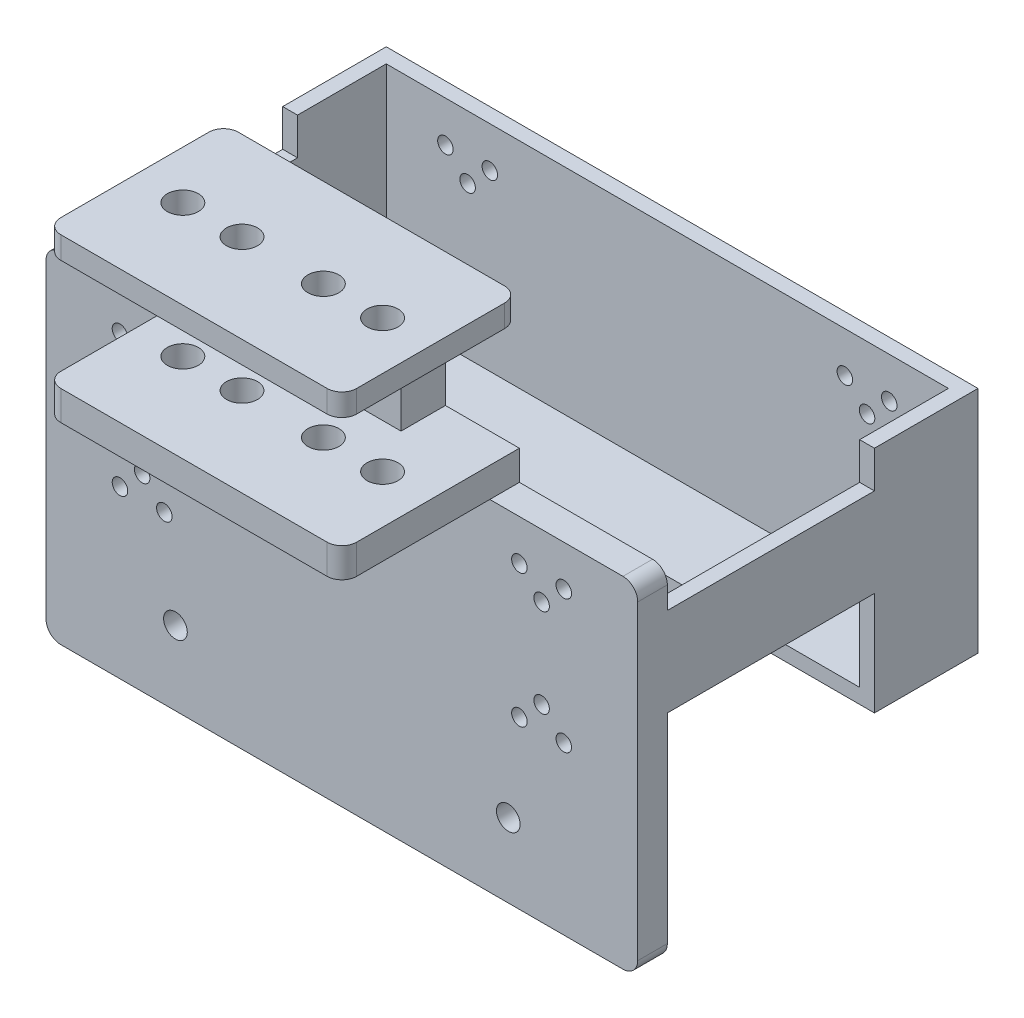
SolidWorks part; units mm, degrees
ref_plane "前视基准面" through (0, 0, 0) normal (0, 0, 1) x (1, 0, 0)
ref_plane "上视基准面" through (0, 0, 0) normal (0, 1, 0) x (1, 0, 0)
ref_plane "右视基准面" through (0, 0, 0) normal (1, 0, 0) x (0, 0, -1)
other "Configuration Table"
sketch "草图1" plane through (0, 0, 0) normal (0, 0, 1) x (1, 0, 0)
  line L1 (-40, 14.5) -> (40, 14.5)
  line L2 (-40, 14.5) -> (-40, -14.5)
  line L3 (-40, -14.5) -> (40, -14.5)
  line L4 (40, 14.5) -> (40, -14.5)
  line L5 (-40, 14.5) -> (40, -14.5) construction
  line L6 (-40, -14.5) -> (40, 14.5) construction
  point P0 (0, 0)
extrude "凸台-拉伸1" add sketch "草图1" along normal blind 2
sketch "草图4" plane through (0, 0, 2) normal (0, 0, 1) x (1, 0, 0)
  line L0 (40, -14.5) -> (40, 14.5) construction
  line L1 (40, 14.5) -> (38, 14.5)
  line L2 (40, 14.5) -> (40, -14.5)
  line L3 (40, -14.5) -> (38, -14.5)
  line L4 (38, 14.5) -> (38, -14.5)
  line L5 (40, 14.5) -> (-40, 14.5) construction
  line L6 (-40, -14.5) -> (40, -14.5) construction
  line L8 (-40, 14.5) -> (-38, 14.5)
  line L9 (-40, 14.5) -> (-40, -14.5)
  line L10 (-40, -14.5) -> (-38, -14.5)
  line L11 (-38, 14.5) -> (-38, -14.5)
  dimension "D1" = 2
  dimension "D2" = 2
extrude "凸台-拉伸2" add sketch "草图4" along normal blind 12
sketch "草图6" plane through (0, -14.5, 0) normal (0, -1, 0) x (1, 0, 0)
  line L1 (-40, 0) -> (40, 0)
  line L2 (-40, 0) -> (-40, 14)
  line L3 (-40, 14) -> (40, 14)
  line L4 (40, 0) -> (40, 14)
extrude "凸台-拉伸4" add sketch "草图6" along normal blind 2
sketch "草图7" plane through (0, 0, 14) normal (0, 0, 1) x (1, 0, 0)
  line L0 (-40, 14.5) -> (-40, -16.5) construction
  line L1 (-40, 9.5) -> (-38, 9.5)
  line L2 (-40, 9.5) -> (-40, -2.5)
  line L3 (-40, -2.5) -> (-38, -2.5)
  line L4 (-38, 9.5) -> (-38, -2.5)
  line L5 (-38, -14.5) -> (-38, 14.5) construction
  line L6 (-38, 14.5) -> (-40, 14.5) construction
  line L7 (38, 14.5) -> (38, -14.5) construction
  line L8 (38, 9.5) -> (40, 9.5)
  line L9 (38, 9.5) -> (38, -2.5)
  line L10 (38, -2.5) -> (40, -2.5)
  line L11 (40, 9.5) -> (40, -2.5)
  line L12 (40, -16.5) -> (40, 14.5) construction
  dimension "D1" = 5
  dimension "D2" = 12
extrude "凸台-拉伸5" add sketch "草图7" along normal blind 28
sketch "草图8" plane through (0, 0, 42) normal (0, 0, 1) x (1, 0, 0)
  line L1 (-40, 14.5) -> (40, 14.5)
  line L2 (-40, 14.5) -> (-40, -16.5)
  line L3 (-40, -16.5) -> (40, -16.5)
  line L4 (40, 14.5) -> (40, -16.5)
extrude "凸台-拉伸6" add sketch "草图8" along normal blind 4
sketch "草图2" plane through (0, 0, 2) normal (0, 0, 1) x (1, 0, 0)
  line L0 (0, 0) -> (27, 0) construction
  line L2 (0, 0) -> (0, 13.1686) construction
  circle A0 centre (-30, 9) radius 1.05
  circle A2 centre (-24, 9) radius 1.05
  circle A3 centre (-27, 6) radius 1.05
  circle A4 centre (-27, -6) radius 1.05
  circle A5 centre (-24, -9) radius 1.05
  circle A7 centre (-30, -9) radius 1.05
  circle A8 centre (27, -6) radius 1.05
  circle A9 centre (30, -9) radius 1.05
  circle A10 centre (24, -9) radius 1.05
  circle A12 centre (27, 6) radius 1.05
  circle A13 centre (30, 9) radius 1.05
  circle A14 centre (24, 9) radius 1.05
  point P3 (27, 6)
  point P5 (27, 9)
  point P6 (30, 9)
  point P7 (24, 9)
  point P8 (24, -9)
  point P9 (27, -6)
  point P10 (27, -9)
  point P11 (30, -9)
  point P14 (-30, -9)
  point P15 (-27, -9)
  point P16 (-27, -6)
  point P17 (-24, -9)
  point P18 (-24, 9)
  point P19 (-30, 9)
  point P20 (-27, 9)
  point P21 (-27, 6)
  dimension "D2" = 27
  dimension "D3" = 6
  dimension "D4" = 3
  dimension "D5" = 3
  dimension "D6" = 3
extrude "切除-拉伸1" cut sketch "草图2" against normal through all and the other way up to surface other way up to face at (0, -1, 46)
sketch "草图12" plane through (0, 14.5, 0) normal (0, 1, 0) x (1, 0, 0)
  line L0 (40, -42) -> (-40, -42) construction
  line L1 (-20, -42) -> (20, -42)
  line L2 (-20, -42) -> (-20, -66)
  line L3 (-20, -66) -> (20, -66)
  line L4 (20, -42) -> (20, -66)
  dimension "D1" = 24
  dimension "D2" = 20
  dimension "D3" = 20
extrude "凸台-拉伸9" add sketch "草图12" along normal blind 4
sketch "草图13" plane through (0, 18.5, 0) normal (0, 1, 0) x (1, 0, 0)
  line L0 (-20, -54) -> (20, -54) construction
  line L1 (-20, -42) -> (-20, -66) construction
  line L2 (20, -66) -> (20, -42) construction
  circle A0 centre (-13.5, -54) radius 2.1
  circle A1 centre (-5.5, -54) radius 2.1
  circle A2 centre (5.5, -54) radius 2.1
  circle A3 centre (13.5, -54) radius 2.1
  point P6 (-5.5, -54)
  point P7 (-13.5, -54)
  point P8 (5.5, -54)
  point P9 (13.5, -54)
  point P10 (0, -54)
  dimension "D1" = 5.5
  dimension "D2" = 5.5
  dimension "D3" = 8
  dimension "D4" = 8
extrude "切除-拉伸3" cut sketch "草图13" against normal up to next and the other way through all
sketch "草图14" plane through (0, 18.5, 0) normal (0, 1, 0) x (1, 0, 0)
  line L0 (-20, -45) -> (20, -45) construction
  line L1 (-20, -42) -> (-20, -66) construction
  line L2 (20, -66) -> (20, -42) construction
  line L3 (20, -42) -> (-20, -42) construction
  line L4 (-10, -48) -> (10, -48)
  line L5 (-10, -48) -> (-10, -42)
  line L6 (-10, -42) -> (10, -42)
  line L7 (10, -48) -> (10, -42)
  line L8 (-10, -48) -> (10, -42) construction
  line L9 (-10, -42) -> (10, -48) construction
  point P0 (-5.5, -54)
  point P8 (0, -45)
  dimension "D1" = 9
  dimension "D2" = 20
extrude "凸台-拉伸10" add sketch "草图14" along normal blind 15
sketch "草图15" plane through (0, 33.5, 0) normal (0, 1, 0) x (1, 0, 0)
  line L0 (10, -42) -> (-10, -42) construction
  line L1 (-20, -42) -> (20, -42)
  line L2 (-20, -42) -> (-20, -66)
  line L3 (-20, -66) -> (20, -66)
  line L4 (20, -42) -> (20, -66)
  point P7 (0, -42)
  point P8 (0, -42)
  dimension "D1" = 40
extrude "凸台-拉伸11" add sketch "草图15" along normal blind 3
sketch "草图16" plane through (0, 36.5, 0) normal (0, 1, 0) x (1, 0, 0)
  line L0 (-20, -54) -> (20, -54) construction
  line L1 (-20, -42) -> (-20, -66) construction
  line L2 (20, -66) -> (20, -42) construction
  circle A0 centre (-13.5, -54) radius 2.1
  circle A1 centre (-5.5, -54) radius 2.1
  circle A2 centre (5.5, -54) radius 2.1
  circle A3 centre (13.5, -54) radius 2.1
  point P6 (-5.5, -54)
  point P7 (-13.5, -54)
  point P8 (5.5, -54)
  point P9 (13.5, -54)
  point P11 (0, -54)
  dimension "D1" = 8
  dimension "D2" = 5.5
  dimension "D3" = 5.5
  dimension "D4" = 8
extrude "切除-拉伸4" cut sketch "草图16" against normal blind 3
sketch "草图21" plane through (0, 0, 46) normal (0, 0, 1) x (1, 0, 0)
  line L0 (0, -16.5) -> (0, 0) construction
  line L1 (-40, 14.5) -> (-40, -16.5) construction
  line L2 (0, -16.5) -> (40, -16.5)
  line L3 (-40, -16.5) -> (40, -16.5) construction
  line L4 (40, -16.5) -> (40, -31.5)
  line L5 (40, -31.5) -> (-40, -31.5)
  line L6 (-40, -31.5) -> (-40, -16.5)
  line L7 (-40, -16.5) -> (0, -16.5)
  line L8 (40, -16.5) -> (40, 14.5) construction
  dimension "D3" = 15
extrude "凸台-拉伸14" add sketch "草图21" against normal up to surface (4 mm away) up to face at (31.05, -9, 42)
sketch "草图22" plane through (0, 0, 46) normal (0, 0, 1) x (1, 0, 0)
  line L0 (-40, -21.5) -> (40, -21.5) construction
  line L4 (-40, -31.5) -> (40, -31.5) construction
  circle A0 centre (-22.5, -21.5) radius 1.6
  circle A1 centre (22.5, -21.5) radius 1.6
  point P6 (22.5, -21.5)
  point P7 (-22.5, -21.5)
  point P8 (0, -21.5)
  dimension "D3" = 10
  dimension "D1" = 22.5
  dimension "D2" = 22.5
extrude "切除-拉伸5" cut sketch "草图22" against normal up to surface (4 mm away)
fillet "圆角1" radius 2 10 edges at (-20, 35, 42) (20, 35, 42) (20, 35, 66) (20, 16.5, 66) (-20, 35, 66) (-20, 16.5, 66) (40, 14.5, 44) (-40, 14.5, 44) (-40, -31.5, 44) (40, -31.5, 44)
